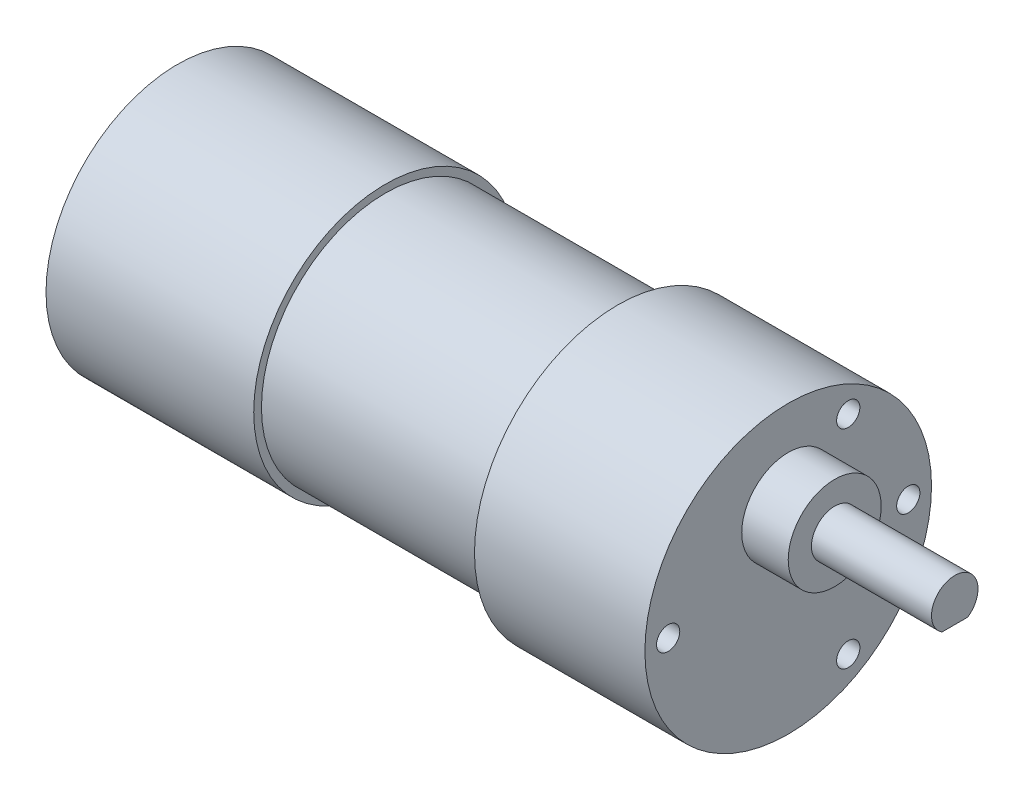
SolidWorks part; units mm, degrees
ref_plane "Plan de face" through (0, 0, 0) normal (0, 0, 1) x (1, 0, 0)
ref_plane "Plan de dessus" through (0, 0, 0) normal (0, 1, 0) x (1, 0, 0)
ref_plane "Plan de droite" through (0, 0, 0) normal (1, 0, 0) x (0, 0, -1)
sketch "Esquisse1" plane through (0, 0, 0) normal (0, 0, 1) x (1, 0, 0)
  line L0 (0, 0) -> (111.3546, 0) construction
  line L1 (0, 0) -> (0, 2)
  line L2 (0, 2) -> (2, 2)
  line L3 (2, 2) -> (2, 16)
  line L4 (2, 16) -> (32, 16)
  line L5 (32, 16) -> (32, 18.5)
  line L6 (32, 18.5) -> (54, 18.5)
  line L7 (54, 18.5) -> (54, 0)
  line L8 (0, 0) -> (54, 0)
  dimension "D1" = 2
  dimension "D2" = 2
  dimension "D3" = 16
  dimension "D4" = 30
  dimension "D5" = 18.5
  dimension "D6" = 22
revolve "Révolution1" add sketch "Esquisse1" angle 360 about L0
sketch "Esquisse2" plane through (54, 0, 0) normal (1, 0, 0) x (0, 0, -1)
  circle A0 centre (0, 7) radius 6
  dimension "D1" = 12
  dimension "D2" = 7
extrude "Boss.-Extru.1" add sketch "Esquisse2" along normal blind 6
sketch "Esquisse3" plane through (60, 0, 0) normal (1, 0, 0) x (0, 0, -1)
  circle A0 centre (0, 7) radius 3
  dimension "D1" = 6
extrude "Boss.-Extru.2" add sketch "Esquisse3" along normal blind 15.5
sketch "Esquisse4" plane through (0, 0, 0) normal (0, 0, 1) x (1, 0, 0)
  line L1 (75.5, 4) -> (63.5, 4)
  line L2 (75.5, 4) -> (75.5, 4.5)
  line L3 (75.5, 4.5) -> (63.5, 4.5)
  line L4 (63.5, 4) -> (63.5, 4.5)
  dimension "D1" = 12
  dimension "D2" = 0.5
extrude "Enlèv. mat.-Extru.1" cut sketch "Esquisse4" against normal mid plane 15.5
sketch "Esquisse5" plane through (54, 0, 0) normal (1, 0, 0) x (0, 0, -1)
  line L0 (0, 0) -> (15.5, 0) construction
  line L1 (0, 0) -> (7.75, 13.4234) construction
  line L2 (0, 0) -> (7.75, -13.4234) construction
  circle A0 centre (0, 0) radius 15.5 construction
  circle A1 centre (15.5, 0) radius 1.5
  circle A2 centre (7.75, 13.4234) radius 1.5
  circle A3 centre (7.75, -13.4234) radius 1.5
  circle A4 centre (-15.5, 0) radius 1.5
  dimension "D1" = 31
  dimension "D2" = 3
  dimension "D3" = 3
  dimension "D4" = 3
  dimension "D5" = 3
  dimension "D6" = 60
  dimension "D7" = 60
extrude "Enlèv. mat.-Extru.2" cut sketch "Esquisse5" against normal blind 3.5
sketch "Esquisse6" plane through (2, 0, 0) normal (-1, 0, 0) x (0, 0, 1)
  line L0 (0, 0) -> (0, 20.209) construction
  line L1 (-1.5, 13.4391) -> (1.5, 13.4391)
  line L2 (-1.5, 13.4391) -> (-1.5, 12.4391)
  line L3 (-1.5, 12.4391) -> (1.5, 12.4391)
  line L4 (1.5, 13.4391) -> (1.5, 12.4391)
  line L9 (13.3059, 0) -> (0, 0) construction
  line L10 (-1.5, -13.4391) -> (-1.5, -12.4391)
  line L11 (-1.5, -13.4391) -> (1.5, -13.4391)
  line L12 (1.5, -13.4391) -> (1.5, -12.4391)
  line L13 (-1.5, -12.4391) -> (1.5, -12.4391)
  dimension "D1" = 3
  dimension "D2" = 1.5
  dimension "D3" = 1
extrude "Boss.-Extru.3" add sketch "Esquisse6" along normal blind 4
sketch "Esquisse7" plane through (2, 0, 0) normal (-1, 0, 0) x (0, 0, 1)
  circle A0 centre (0, 0) radius 17
  dimension "D1" = 34
extrude "Boss.-Extru.4" add sketch "Esquisse7" along normal blind 26.8133
